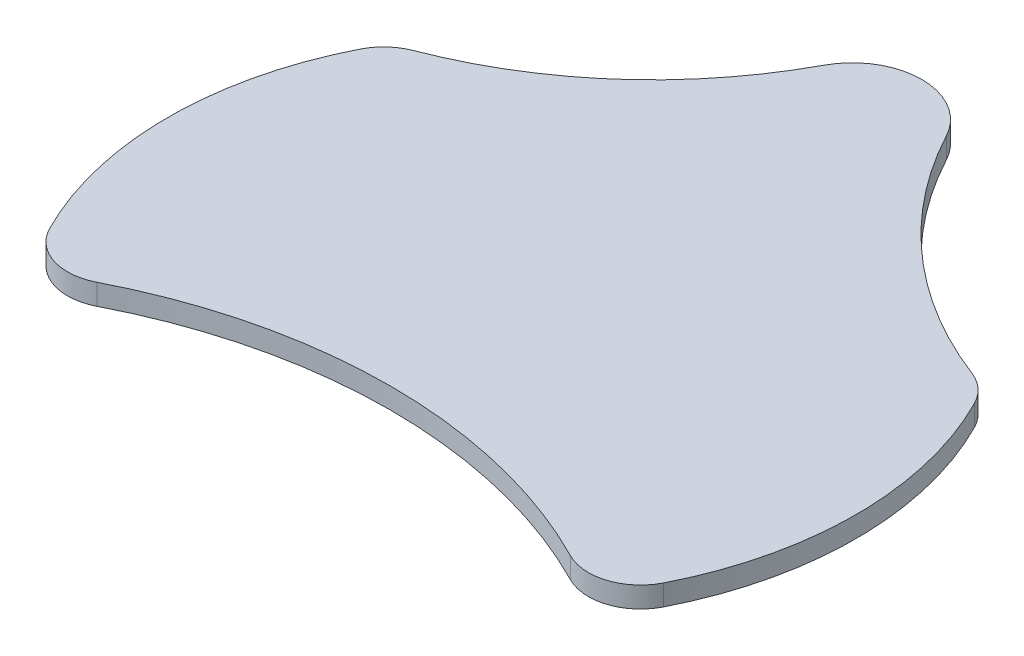
SolidWorks part; units mm, degrees
ref_plane "Front Plane" through (0, 0, 0) normal (0, 0, 1) x (1, 0, 0)
ref_plane "Top Plane" through (0, 0, 0) normal (0, 1, 0) x (1, 0, 0)
ref_plane "Right Plane" through (0, 0, 0) normal (1, 0, 0) x (0, 0, -1)
sketch "Sketch1" plane through (0, 0, 0) normal (0, 1, 0) x (1, 0, 0)
  line L0 (4.018, 0) -> (-26.2688, 0) construction
  line L1 (0, 8.2176) -> (0, -12.6559) construction
  line L2 (-37.5, 12.3843) -> (-37.5, -26.076) construction
  line L3 (37.5, 8.5648) -> (37.5, -21.0867) construction
  line L4 (-49.107, 30) -> (50.7773, 30) construction
  line L5 (-56.0514, -38) -> (44.643, -38) construction
  circle A0 centre (-37.5, -38) radius 7.5
  circle A1 centre (37.5, -38) radius 7.5
  circle A2 centre (-37.5, 0) radius 7.5
  circle A3 centre (37.5, 0) radius 7.5
  circle A4 centre (0, 30) radius 10
  circle A5 centre (0, -19) radius 49.5387
  circle A7 centre (0, -111.4847) radius 75
  circle A8 centre (-61.7333, 63) radius 60
  circle A9 centre (61.7333, 63) radius 60
  dimension "D6" = 15
  dimension "spine_width" = 20
  dimension "D9" = 120
  dimension "stomach_round" = 150
  dimension "body_width" = 75
  dimension "D2" = 37.5
  dimension "shoulder_to_spine" = 30
  dimension "shoulder_to_foot" = 38
extrude "Boss-Extrude1" add sketch "Sketch1" along normal blind 3 contours A2 | A3 | A1 | A0 | A9 A5 A4 A8 A2 A0 A7 A1 A3 | A5 A4 | A9 A4 A5 | A8 A5 A4 | A4 A5
equation "\"D2@Sketch1\"=\"body_width@Sketch1\" / 2"
